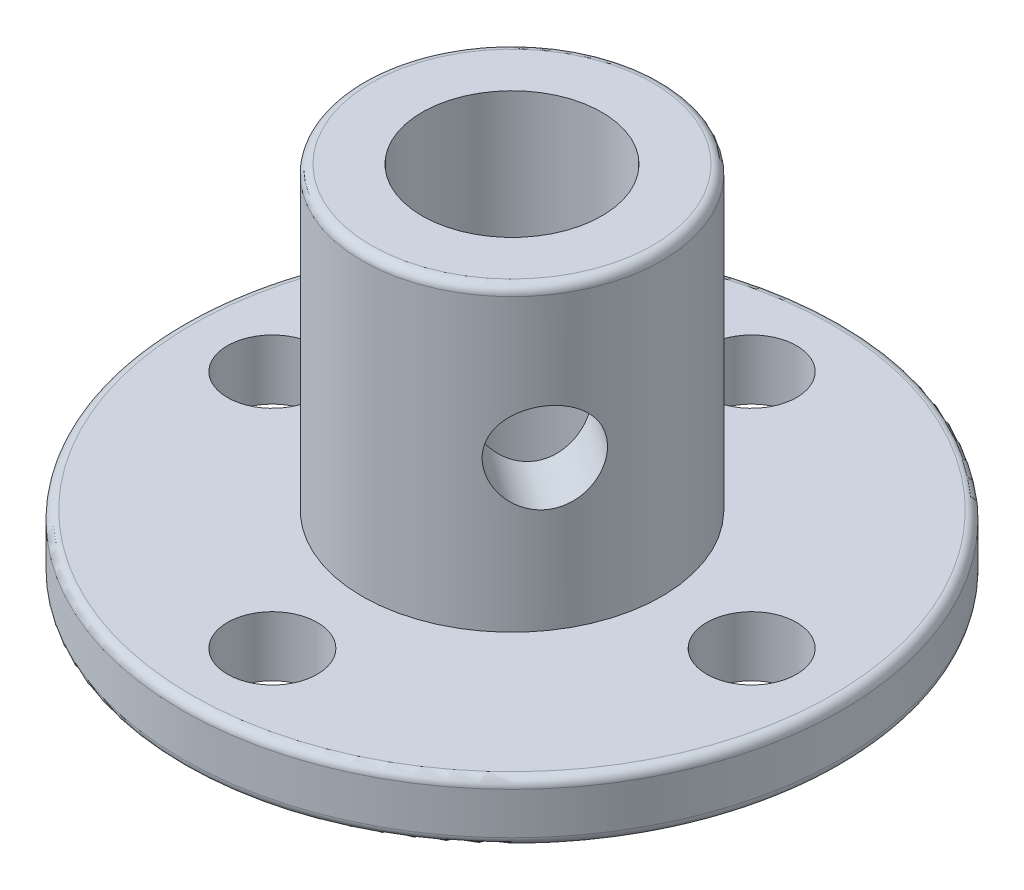
SolidWorks part; units mm, degrees
ref_plane "Front Plane" through (0, 0, 0) normal (0, 0, 1) x (1, 0, 0)
ref_plane "Top Plane" through (0, 0, 0) normal (0, 1, 0) x (1, 0, 0)
ref_plane "Right Plane" through (0, 0, 0) normal (1, 0, 0) x (0, 0, -1)
sketch "Sketch1" plane through (0, 0, 0) normal (0, 1, 0) x (1, 0, 0)
  circle A1 centre (0, 0) radius 5
  dimension "D2" = 10
extrude "Boss-Extrude2" add sketch "Sketch1" along normal blind 12
sketch "Sketch3" plane through (0, 0, 0) normal (0, 1, 0) x (1, 0, 0)
  circle A0 centre (0, 0) radius 11
  dimension "D1" = 22
extrude "Boss-Extrude3" add sketch "Sketch3" along normal blind 2
sketch "Sketch4" plane through (0, 0, 0) normal (0, 1, 0) x (1, 0, 0)
  circle A0 centre (0, 0) radius 3
  dimension "D1" = 6
extrude "Cut-Extrude1" cut sketch "Sketch4" along normal blind 12
sketch "Sketch5" plane through (0, 2, 0) normal (0, 1, 0) x (1, 0, 0)
  line L0 (0, 0) -> (0, 8) construction
  circle A0 centre (0, 8) radius 1.5
  circle A1 centre (8, 0) radius 1.5
  circle A2 centre (0, -8) radius 1.5
  circle A3 centre (-8, 0) radius 1.5
  point P13 (0, 0)
  dimension "D2" = 3
  dimension "D1" = 8
  dimension "D3" = 4
extrude "Cut-Extrude2" cut sketch "Sketch5" against normal blind 2
fillet "Fillet1" radius 0.3 3 edges at (0, 12, 5) (0, 0, 11) (0, 2, 11)
ref_plane "Plane1" through (4.0625, 0, 2.9148) normal (0.8125, 0, 0.583) x (0.583, 0, -0.8125)
sketch "Sketch7" plane through (4.0625, 0, 2.9148) normal (0.8125, 0, 0.583) x (0.583, 0, -0.8125)
  line L0 (0, 0) -> (0, 7) construction
  circle A0 centre (0, 7) radius 1.5
  dimension "D2" = 3
  dimension "D1" = 7
extrude "Cut-Extrude3" cut sketch "Sketch7" against normal blind 4
